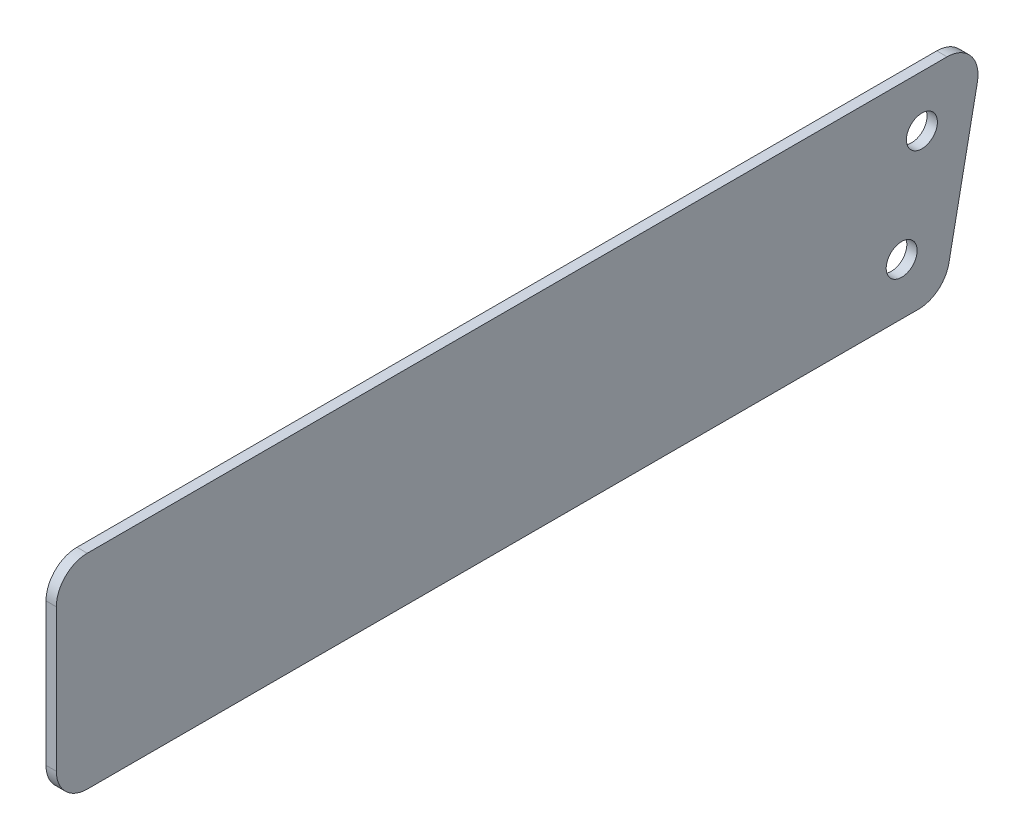
SolidWorks part; units mm, degrees
material "1060 合金"
ref_plane "正面" through (0, 0, 0) normal (0, 0, 1) x (1, 0, 0)
ref_plane "平面" through (0, 0, 0) normal (0, 1, 0) x (1, 0, 0)
ref_plane "右側面" through (0, 0, 0) normal (1, 0, 0) x (0, 0, -1)
sketch "ｽｹｯﾁ1" plane through (0, 0, 0) normal (1, 0, 0) x (0, 0, -1)
  line L0 (39.901, 9.9029) -> (35.9398, -9.9029) construction
  line L1 (-45, -9.9029) -> (45, -9.9029)
  line L2 (-45, -9.9029) -> (-45, 9.9029)
  line L3 (-45, 9.9029) -> (45, 9.9029)
  line L4 (45, -9.9029) -> (45, 9.9029)
  line L5 (-45, -9.9029) -> (45, 9.9029) construction
  line L6 (-45, 9.9029) -> (45, -9.9029) construction
  line L7 (45, 9.9029) -> (41.0388, -9.9029)
  circle A0 centre (38.901, 4.9029) radius 1.5
  circle A1 centre (36.9398, -4.9029) radius 1.5
  point P0 (0, 0)
  point P14 (100.7584, 9.9029)
  dimension "D2" = 10
  dimension "D3" = 5
  dimension "D4" = 5
  dimension "D5" = 3
  dimension "D1" = 101.31
  dimension "D6" = 5
  dimension "D7" = 90
extrude "ﾎﾞｽ - 押し出し1" add sketch "ｽｹｯﾁ1" along normal blind 1 contours L7 L3 L2 L1 A1 A0
fillet "ﾌｨﾚｯﾄ1" radius 3 4 edges at (0.5, -9.9029, -41.0388) (0.5, 9.9029, -45) (0.5, -9.9029, 45) (0.5, 9.9029, 45)
